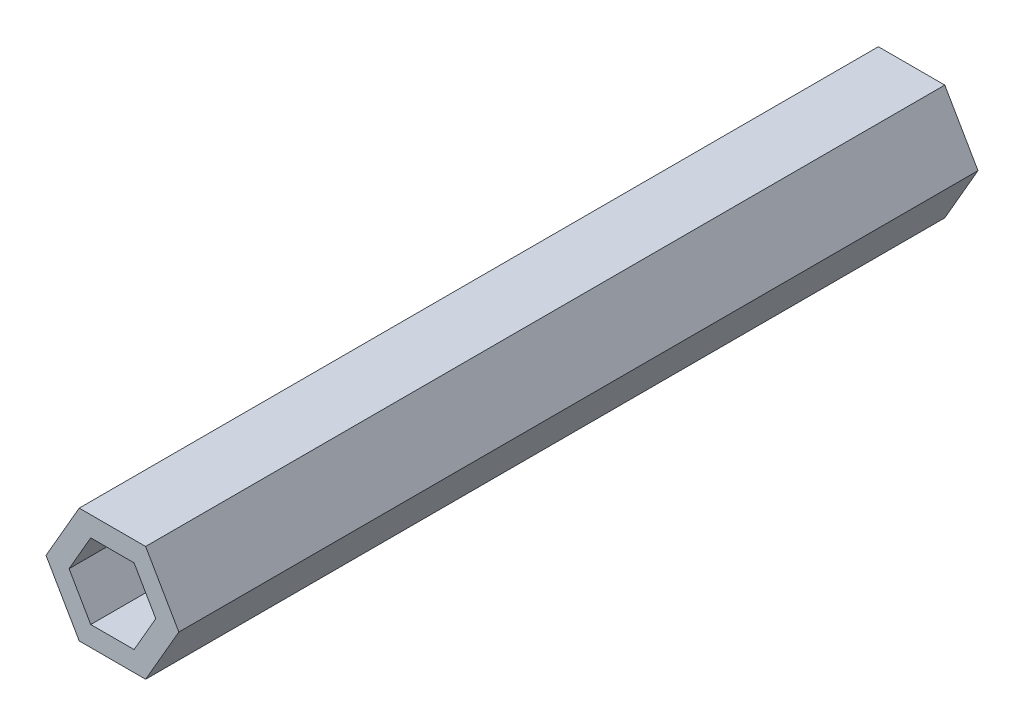
SolidWorks part; units mm, degrees
ref_plane "Front Plane" through (0, 0, 0) normal (0, 0, 1) x (1, 0, 0)
ref_plane "Top Plane" through (0, 0, 0) normal (0, 1, 0) x (1, 0, 0)
ref_plane "Right Plane" through (0, 0, 0) normal (1, 0, 0) x (0, 0, -1)
sketch "Sketch1" plane through (0, 0, 0) normal (0, 0, 1) x (1, 0, 0)
  line L0 (-8.4439, 0) -> (-4.222, -7.3127)
  line L1 (-5.511, 0) -> (-2.7555, -4.7727)
  line L2 (-2.7555, -4.7727) -> (2.7555, -4.7727)
  line L3 (2.7555, -4.7727) -> (5.511, 0)
  line L4 (5.511, 0) -> (2.7555, 4.7727)
  line L5 (2.7555, 4.7727) -> (-2.7555, 4.7727)
  line L6 (-2.7555, 4.7727) -> (-5.511, 0)
  line L7 (-4.222, -7.3127) -> (4.222, -7.3127)
  line L8 (4.222, -7.3127) -> (8.4439, 0)
  line L9 (8.4439, 0) -> (4.222, 7.3127)
  line L10 (4.222, 7.3127) -> (-4.222, 7.3127)
  line L11 (-4.222, 7.3127) -> (-8.4439, 0)
  circle A0 centre (0, 0) radius 4.7727 construction
  dimension "D1" = 2.54
extrude "Boss-Extrude1" add sketch "Sketch1" along normal blind 101.6
